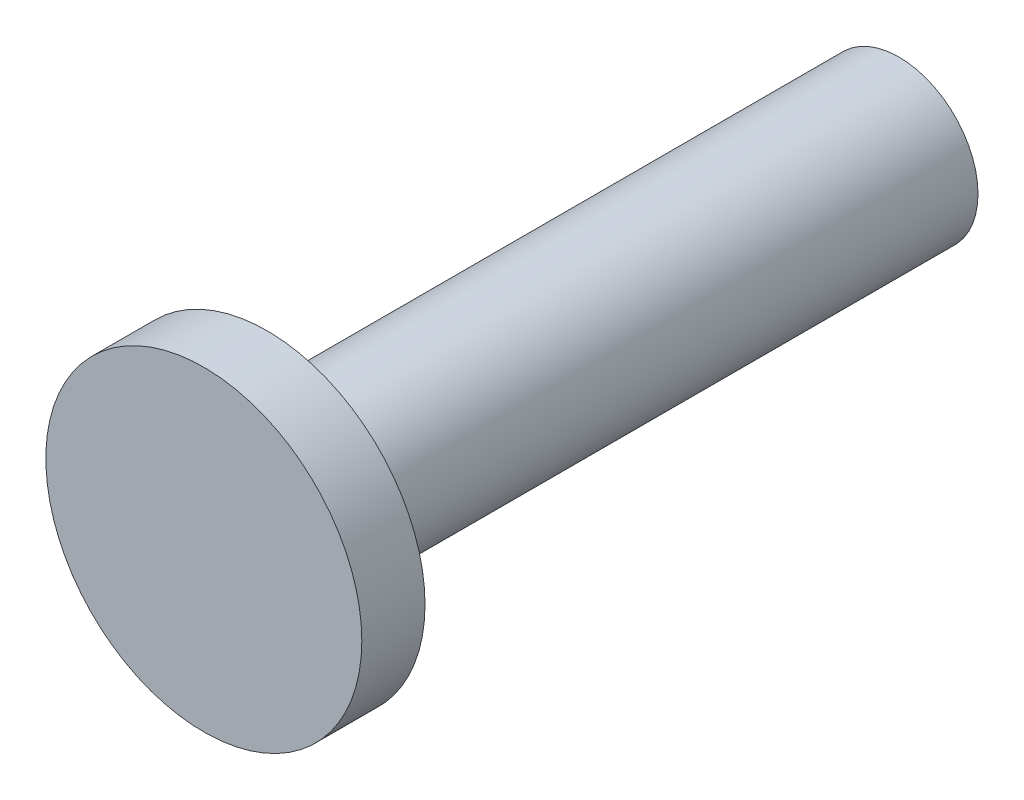
SolidWorks part; units mm, degrees
material "Galvanized Steel"
ref_plane "Front Plane" through (0, 0, 0) normal (0, 0, 1) x (1, 0, 0)
ref_plane "Top Plane" through (0, 0, 0) normal (0, 1, 0) x (1, 0, 0)
ref_plane "Right Plane" through (0, 0, 0) normal (1, 0, 0) x (0, 0, -1)
sketch "Sketch1" plane through (0, 0, 0) normal (0, 0, 1) x (1, 0, 0)
  circle A0 centre (-16.531, 16.8128) radius 3.175
  point P2 (0, 0)
  point P3 (0, 0)
extrude "Boss-Extrude1" add sketch "Sketch1" along normal blind 25.4
sketch "Sketch4" plane through (0, 0, 25.4) normal (0, 0, 1) x (1, 0, 0)
  circle A0 centre (-16.531, 16.8128) radius 6.35
extrude "Boss-Extrude2" add sketch "Sketch4" along normal blind 2.54
